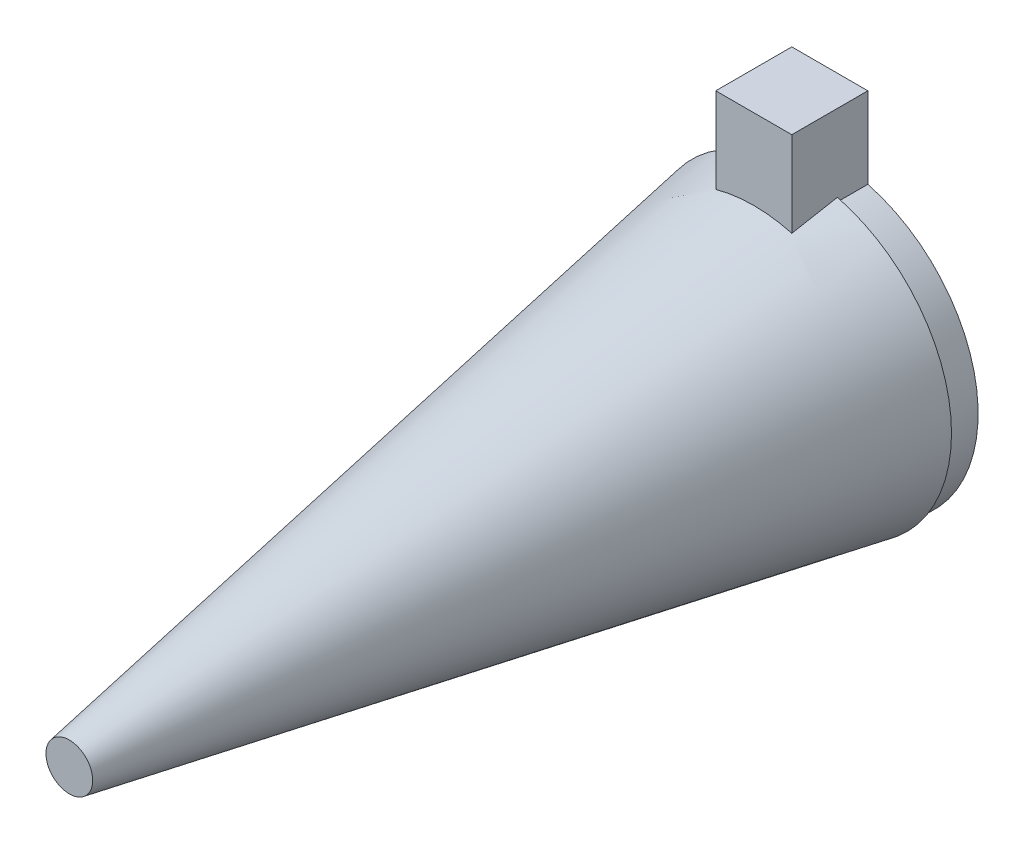
SolidWorks part; units mm, degrees
ref_plane "Front Plane" through (0, 0, 0) normal (0, 0, 1) x (1, 0, 0)
ref_plane "Top Plane" through (0, 0, 0) normal (0, 1, 0) x (1, 0, 0)
ref_plane "Right Plane" through (0, 0, 0) normal (1, 0, 0) x (0, 0, -1)
sketch "Sketch1" plane through (0, 0, 0) normal (0, 0, 1) x (1, 0, 0)
  line L0 (4.2341, 2.5705) -> (4.2341, 0.2705) construction
  circle A0 centre (4.2341, -7.1795) radius 9.75
  circle A2 centre (4.2341, 0.2705) radius 0.5
  circle A3 centre (9.502, -1.9116) radius 0.5
  circle A4 centre (11.6841, -7.1795) radius 0.5
  circle A5 centre (9.502, -12.4474) radius 0.5
  circle A6 centre (4.2341, -14.6295) radius 0.5
  circle A7 centre (-1.0339, -12.4474) radius 0.5
  circle A8 centre (-3.2159, -7.1795) radius 0.5
  circle A9 centre (-1.0339, -1.9116) radius 0.5
  point P15 (4.2341, -7.1795)
extrude "Boss-Extrude1" add sketch "Sketch1" along normal blind 2
sketch "Sketch3" plane through (0, 0, 2) normal (0, 0, 1) x (1, 0, 0)
  circle A0 centre (4.2341, -7.1795) radius 10
extrude "Boss-Extrude2" add sketch "Sketch3" along normal blind 48 draft 10
sketch "Sketch4" plane through (0, 0, 0) normal (0, 0, -1) x (-1, 0, 0)
  line L0 (-4.2341, 2.5705) -> (-4.2341, 7.5705)
  line L1 (-6.7341, 7.5705) -> (-1.7341, 7.5705)
  line L2 (-1.7341, 7.5705) -> (-1.7341, 2.2445)
  line L3 (-6.7341, 7.5705) -> (-6.7341, 2.2445)
  circle A0 centre (-4.2341, -7.1795) radius 9.75 construction
  circle A1 centre (-4.2341, -7.1795) radius 9.75 construction
  arc A2 (-1.7341, 2.2445) -> (-6.7341, 2.2445) centre (-4.2341, -7.1795) ccw
  circle M6 centre (-4.2341, -7.1795) radius 9.75
extrude "Boss-Extrude3" add sketch "Sketch4" against normal blind 5 contours L1 L3 L0 M6 | L2 L1 L0 M6
sketch "Sketch5" plane through (0, 7.5705, 0) normal (0, 1, 0) x (1, 0, 0)
  line L4 (6.7341, 0) -> (1.7341, 0)
  line L5 (1.7341, 0) -> (1.7341, -5)
  line L6 (1.7341, -5) -> (6.7341, -5)
  line L7 (6.7341, -5) -> (6.7341, 0)
  line L8 (6.7341, 0) -> (1.7341, 0)
  line L9 (1.7341, 0) -> (1.7341, -5)
  line L10 (1.7341, -5) -> (6.7341, -5)
  line L11 (6.7341, -5) -> (6.7341, 0)
  dimension "D1" = 0
extrude "Boss-Extrude4" add sketch "Sketch5" against normal blind 6
